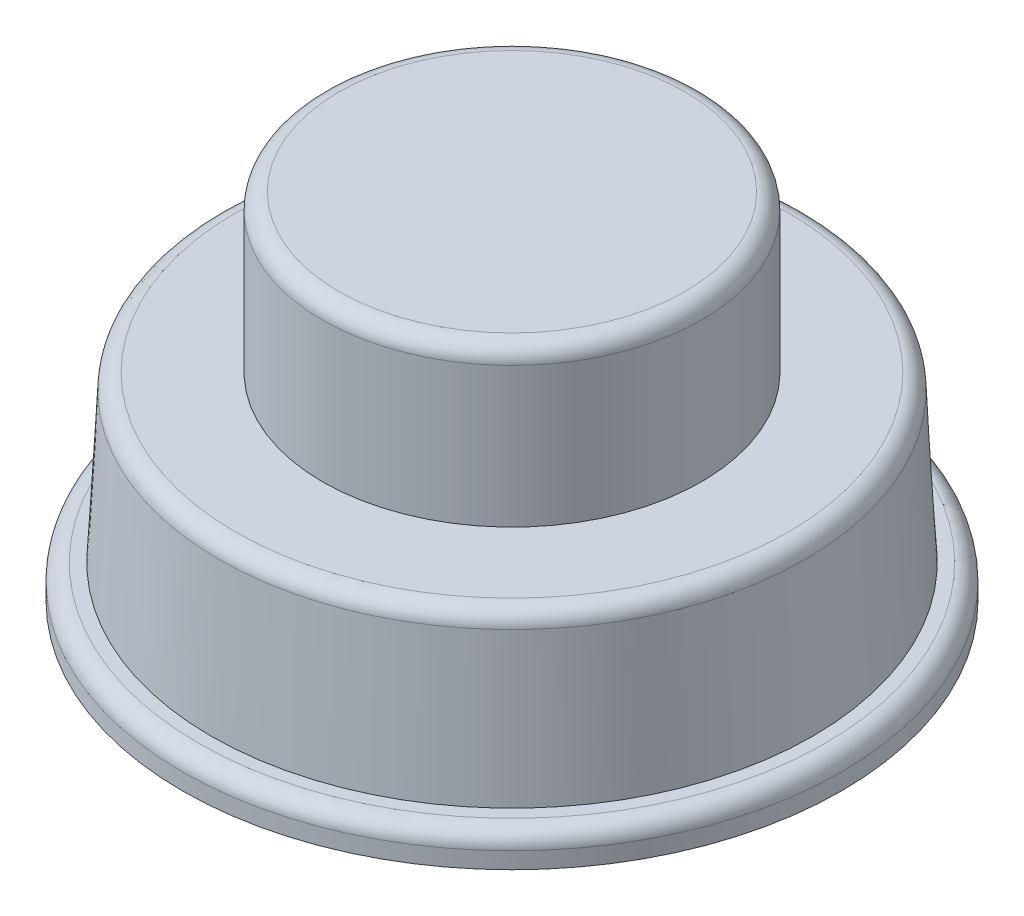
SolidWorks part; units mm, degrees
ref_plane "Front Plane" through (0, 0, 0) normal (0, 0, 1) x (1, 0, 0)
ref_plane "Top Plane" through (0, 0, 0) normal (0, 1, 0) x (1, 0, 0)
ref_plane "Right Plane" through (0, 0, 0) normal (1, 0, 0) x (0, 0, -1)
sketch "Sketch1" plane through (0, 0, 0) normal (0, 1, 0) x (1, 0, 0)
  circle A0 centre (0, 0) radius 20
  dimension "D1" = 40
extrude "Boss-Extrude1" add sketch "Sketch1" along normal blind 2
sketch "Sketch2" plane through (0, 2, 0) normal (0, 1, 0) x (1, 0, 0)
  circle A0 centre (0, 0) radius 18.25
  dimension "D1" = 36.5
extrude "Boss-Extrude2" add sketch "Sketch2" along normal blind 10 draft 3
sketch "Sketch3" plane through (0, 12, 0) normal (0, 1, 0) x (1, 0, 0)
  circle A0 centre (0, 0) radius 11.5
  dimension "D1" = 23
extrude "Boss-Extrude3" add sketch "Sketch3" along normal offset from surface (9.5 mm away) 21.5 up to face at (0, 0, 20)
fillet "Fillet1" radius 1 3 edges at (0, 2, 20) (0, 12, 17.7259) (0, 21.5, 11.5)
